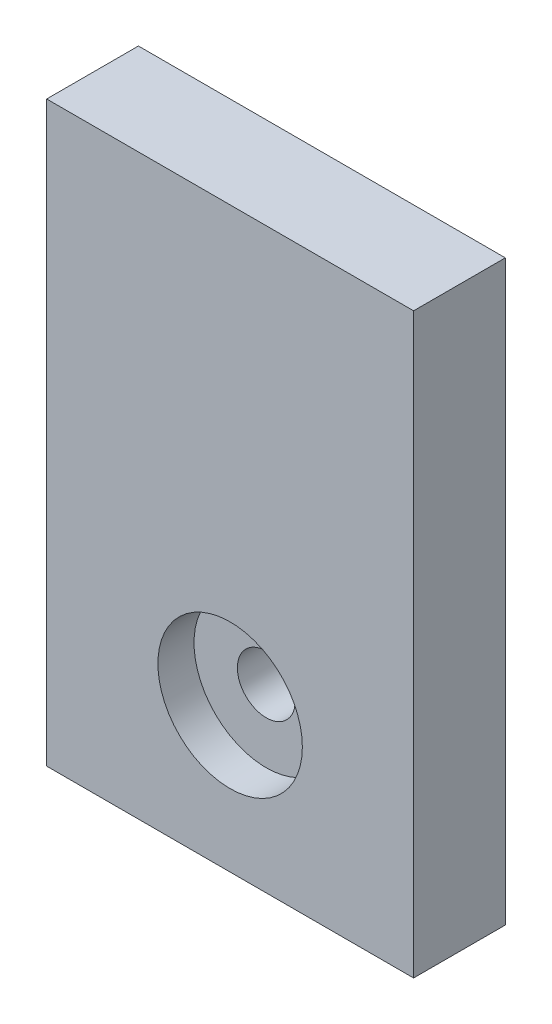
SolidWorks part; units mm, degrees
material "Aleación 1060"
ref_plane "Alzado" through (0, 0, 0) normal (0, 0, 1) x (1, 0, 0)
ref_plane "Planta" through (0, 0, 0) normal (0, 1, 0) x (1, 0, 0)
ref_plane "Vista lateral" through (0, 0, 0) normal (1, 0, 0) x (0, 0, -1)
sketch "Croquis1" plane through (0, 0, 0) normal (0, 0, 1) x (1, 0, 0)
  line L1 (25.4, -40) -> (-25.4, -40)
  line L2 (25.4, -40) -> (25.4, 40)
  line L3 (25.4, 40) -> (-25.4, 40)
  line L4 (-25.4, -40) -> (-25.4, 40)
  line L5 (25.4, -40) -> (-25.4, 40) construction
  line L6 (25.4, 40) -> (-25.4, -40) construction
  circle A0 centre (0, -20) radius 4
  point P0 (0, 0)
  dimension "D3" = 8
  dimension "D1" = 50.8
  dimension "D2" = 80
  dimension "D4" = 20
extrude "Saliente-Extruir1" add sketch "Croquis1" along normal blind 12.7
sketch "Croquis2" plane through (0, 0, 12.7) normal (0, 0, 1) x (1, 0, 0)
  circle A0 centre (0, -20) radius 10
  dimension "D1" = 20
extrude "Cortar-Extruir1" cut sketch "Croquis2" against normal blind 5
